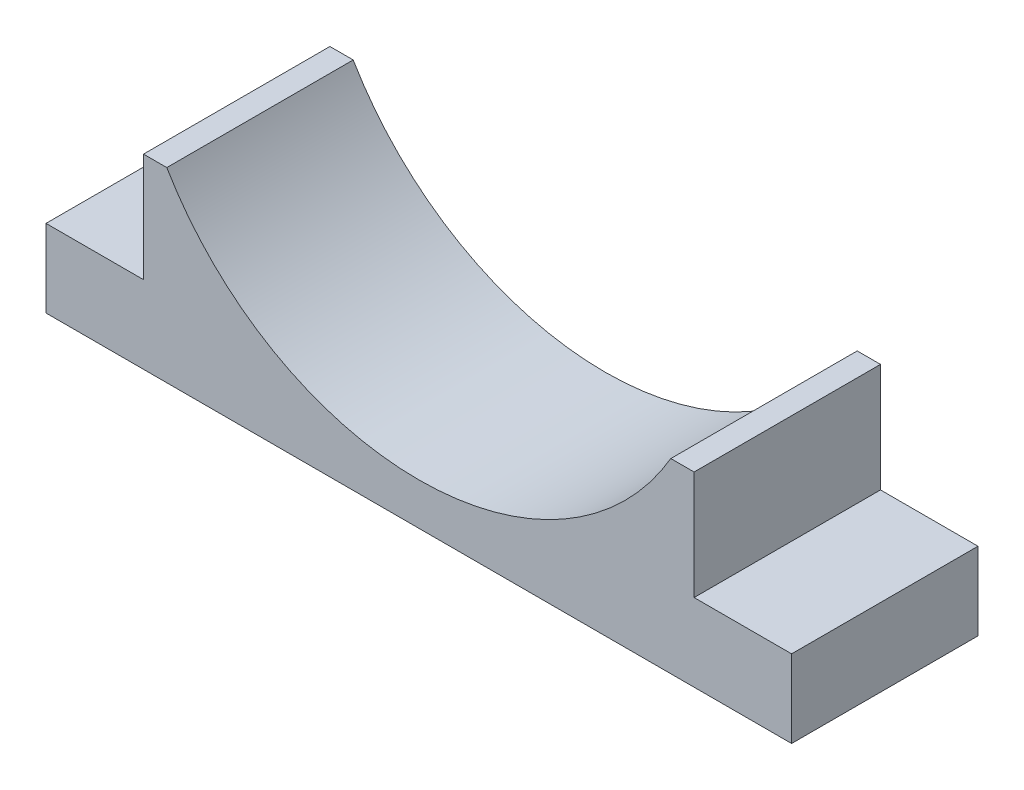
SolidWorks part; units mm, degrees
ref_plane "Front Plane" through (0, 0, 0) normal (0, 0, 1) x (1, 0, 0)
ref_plane "Top Plane" through (0, 0, 0) normal (0, 1, 0) x (1, 0, 0)
ref_plane "Right Plane" through (0, 0, 0) normal (1, 0, 0) x (0, 0, -1)
sketch "Cylindrical motor seat profile" plane through (0, 0, 0) normal (0, 0, 1) x (1, 0, 0)
  line L0 (-24, 7) -> (24, 7)
  line L1 (24, 7) -> (24, 12)
  line L2 (24, 12) -> (17.7231, 12)
  line L3 (17.7231, 12) -> (17.7231, 19)
  line L4 (17.7231, 19) -> (16.2231, 19)
  line L5 (-16.2231, 19) -> (-17.7231, 19)
  line L6 (-17.7231, 19) -> (-17.7231, 12)
  line L7 (-17.7231, 12) -> (-24, 12)
  line L8 (-24, 12) -> (-24, 7)
  arc A0 (16.2231, 19) -> (-16.2231, 19) centre (0, 28.5) cw
extrude "Cylindrical motor seat" add sketch "Cylindrical motor seat profile" along normal blind 12
